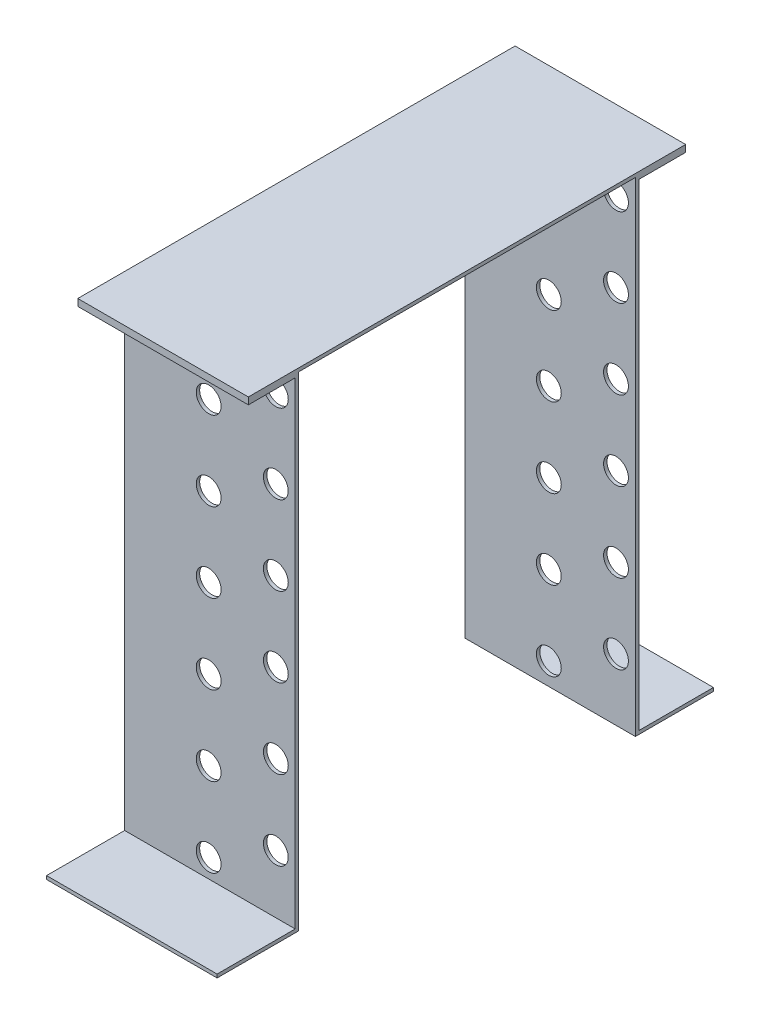
SolidWorks part; units mm, degrees
ref_plane "Front" through (0, 0, 0) normal (0, 0, 1) x (1, 0, 0)
ref_plane "Top" through (0, 0, 0) normal (0, 1, 0) x (1, 0, 0)
ref_plane "Right" through (0, 0, 0) normal (1, 0, 0) x (0, 0, -1)
sketch "Esboço1" plane through (0, 0, 0) normal (1, 0, 0) x (0, 0, -1)
  line L0 (0, 0) -> (25, 0)
  line L1 (0, 0) -> (0, -1.1)
  line L2 (0, -1.1) -> (26.1, -1.1)
  line L3 (26.1, -1.1) -> (26.1, 153.9)
  line L4 (25, 0) -> (25, 152.8)
  line L6 (25, 152.8) -> (10, 152.8)
  line L7 (10, 152.8) -> (10, 153.9)
  line L9 (10, 153.9) -> (10, 155)
  line L10 (10, 155) -> (26.1, 155)
  line L12 (135, 152.8) -> (150, 152.8)
  line L13 (150, 152.8) -> (150, 155)
  line L14 (135, 152.8) -> (135, 0)
  line L17 (133.9, 153.9) -> (133.9, -1.1)
  line L19 (133.9, 155) -> (150, 155)
  line L20 (133.9, -1.1) -> (158.9, -1.1)
  line L21 (135, 0) -> (158.9, 0)
  line L22 (158.9, 0) -> (158.9, -1.1)
  line L23 (26.1, 155) -> (133.9, 155)
  line L24 (26.1, 153.9) -> (133.9, 153.9)
extrude "Ressalto-extrusão1" add sketch "Esboço1" along normal blind 54.6
sketch "Esboço2" plane through (0, 0, -25) normal (0, 0, 1) x (1, 0, 0)
  circle A0 centre (26.9, 6) radius 3.98
  circle A1 centre (48.4, 18.7) radius 3.98
  circle A2 centre (26.9, 31.4) radius 3.98
  circle A3 centre (48.4, 44.1) radius 3.98
  circle A4 centre (26.9, 56.8) radius 3.98
  circle A5 centre (48.4, 69.5) radius 3.98
  circle A6 centre (26.9, 82.2) radius 3.98
  circle A7 centre (48.4, 94.9) radius 3.98
  circle A8 centre (26.9, 107.6) radius 3.98
  circle A9 centre (48.4, 120.3) radius 3.98
  circle A10 centre (26.9, 133) radius 3.98
  circle A11 centre (48.4, 145.7) radius 3.98
  dimension "D1" = 6
extrude "Corte-extrusão1" cut sketch "Esboço2" against normal through all
